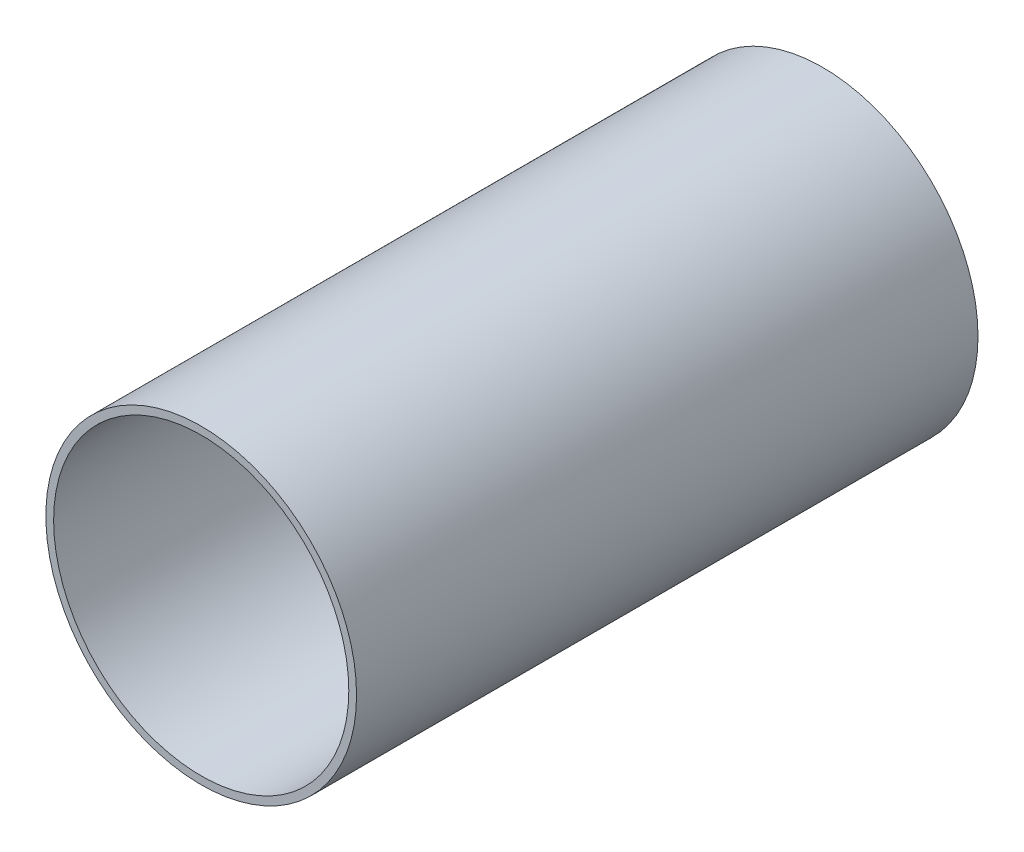
SolidWorks part; units mm, degrees
other "标注1"
sketch "草图5" plane through (100, 100, 200) normal (0.461, 0.308, 0.8323) x (-0.7479, 0.6396, 0.1776)
material "1060 合金"
ref_plane "前视基准面" through (0, 0, 0) normal (0, 0, 1) x (1, 0, 0)
ref_plane "上视基准面" through (0, 0, 0) normal (0, 1, 0) x (1, 0, 0)
ref_plane "右视基准面" through (0, 0, 0) normal (1, 0, 0) x (0, 0, -1)
other "Configuration Table"
sketch "草图6" plane through (0, 0, 0) normal (0, 0, 1) x (1, 0, 0)
  circle A0 centre (0, 0) radius 100
  circle A1 centre (0, 0) radius 95
extrude "凸台-拉伸1" add sketch "草图6" along normal blind 400
